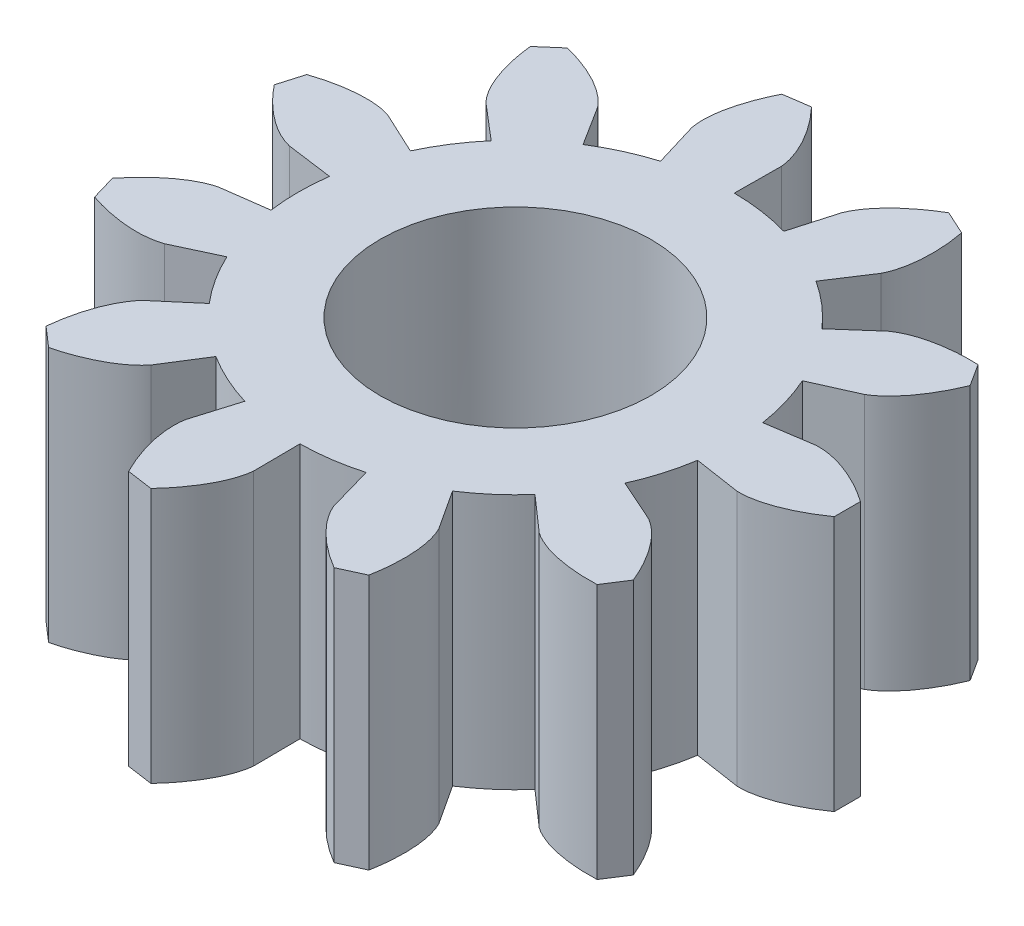
SolidWorks part; units mm, degrees
ref_plane "Front Plane" through (0, 0, 0) normal (0, 0, 1) x (1, 0, 0)
ref_plane "Top Plane" through (0, 0, 0) normal (0, 1, 0) x (1, 0, 0)
ref_plane "Right Plane" through (0, 0, 0) normal (1, 0, 0) x (0, 0, -1)
ref_plane "Plane1" through (0, -5, 0) normal (0, -1, 0) x (1, 0, 0)
sketch "Sketch1" plane through (0, -5, 0) normal (0, -1, 0) x (1, 0, 0)
  line L0 (3.1902, -2.808) -> (3.8796, -3.4147)
  line L1 (5.3253, -3.727) -> (5.6025, -3.2958)
  line L2 (4.7178, -2.1104) -> (3.8795, -1.7354)
  line L3 (4.2019, -0.6375) -> (5.1098, -0.7752)
  line L4 (6.4949, -0.2563) -> (6.4949, 0.2563)
  line L5 (5.1098, 0.7752) -> (4.2019, 0.6375)
  line L6 (3.8795, 1.7354) -> (4.7178, 2.1104)
  line L7 (5.6025, 3.2958) -> (5.3253, 3.727)
  line L8 (3.8796, 3.4147) -> (3.1902, 2.808)
  line L9 (2.3254, 3.5574) -> (2.8279, 4.326)
  line L10 (2.9312, 5.8015) -> (2.465, 6.0145)
  line L11 (1.4175, 4.9701) -> (1.1657, 4.087)
  line L12 (0.033, 4.2499) -> (0.0401, 5.1682)
  line L13 (-0.6706, 6.4653) -> (-1.178, 6.3924)
  line L14 (-1.4945, 4.9475) -> (-1.229, 4.0684)
  line L15 (-2.2699, 3.5931) -> (-2.7604, 4.3694)
  line L16 (-4.0596, 5.0764) -> (-4.447, 4.7407)
  line L17 (-3.9321, 3.3541) -> (-3.2334, 2.7581)
  line L18 (-3.8521, 1.7955) -> (-4.6844, 2.1834)
  line L19 (-6.1596, 2.0758) -> (-6.3041, 1.5839)
  line L20 (-5.1213, 0.6958) -> (-4.2113, 0.5722)
  line L21 (-4.2113, -0.5722) -> (-5.1213, -0.6958)
  line L22 (-6.3041, -1.5839) -> (-6.1596, -2.0758)
  line L23 (-4.6844, -2.1834) -> (-3.8521, -1.7955)
  line L24 (-3.2334, -2.7581) -> (-3.9321, -3.3541)
  line L25 (-4.447, -4.7407) -> (-4.0596, -5.0764)
  line L26 (-2.7604, -4.3694) -> (-2.2699, -3.5931)
  line L27 (-1.229, -4.0684) -> (-1.4945, -4.9475)
  line L28 (-1.178, -6.3924) -> (-0.6706, -6.4653)
  line L29 (0.0401, -5.1682) -> (0.033, -4.2499)
  line L30 (1.1657, -4.087) -> (1.4175, -4.9701)
  line L31 (2.465, -6.0145) -> (2.9312, -5.8015)
  line L32 (2.8279, -4.326) -> (2.3254, -3.5574)
  arc A0 (2.3254, -3.5574) -> (3.1902, -2.808) centre (0, 0) ccw
  arc A1 (3.8795, -1.7354) -> (4.2019, -0.6375) centre (0, 0) ccw
  arc A2 (4.2019, 0.6375) -> (3.8795, 1.7354) centre (0, 0) ccw
  arc A3 (3.1902, 2.808) -> (2.3254, 3.5574) centre (0, 0) ccw
  arc A4 (1.1657, 4.087) -> (0.033, 4.2499) centre (0, 0) ccw
  arc A5 (-1.229, 4.0684) -> (-2.2699, 3.5931) centre (0, 0) ccw
  arc A6 (-3.2334, 2.7581) -> (-3.8521, 1.7955) centre (0, 0) ccw
  arc A7 (-4.2113, 0.5722) -> (-4.2113, -0.5722) centre (0, 0) ccw
  arc A8 (-3.8521, -1.7955) -> (-3.2334, -2.7581) centre (0, 0) ccw
  arc A9 (-2.2699, -3.5931) -> (-1.229, -4.0684) centre (0, 0) ccw
  arc A10 (0.033, -4.2499) -> (1.1657, -4.087) centre (0, 0) ccw
  ellipse E0 centre (5.2837, -2.9889) end of major axis (6.9215, -2.923) minor radius 0.7393 (3.8796, -3.4147) -> (5.3253, -3.727) ccw
  ellipse E1 centre (4.9239, -3.5316) end of major axis (5.5451, -5.0133) minor radius 0.7173 (5.6025, -3.2958) -> (4.7178, -2.1104) ccw
  ellipse E2 centre (6.0609, 0.3422) end of major axis (7.403, 1.283) minor radius 0.7393 (5.1098, -0.7752) -> (6.4949, -0.2563) ccw
  ellipse E3 centre (6.0515, -0.3089) end of major axis (7.3752, -1.2195) minor radius 0.7173 (6.4949, 0.2563) -> (5.1098, 0.7752) ccw
  ellipse E4 centre (4.9137, 3.5646) end of major axis (4.2933, 2.0475) minor radius 0.7393 (4.7178, 2.1104) -> (5.6025, 3.2958) ccw
  ellipse E5 centre (5.2579, 3.0118) end of major axis (6.8637, 2.9614) minor radius 0.7173 (5.3253, 3.727) -> (3.8796, 3.4147) ccw
  ellipse E6 centre (2.2065, 5.6553) end of major axis (2.5048, 4.0436) minor radius 0.7393 (2.8279, 4.326) -> (2.9312, 5.8015) ccw
  ellipse E7 centre (2.7949, 5.3763) end of major axis (4.1731, 6.2021) minor radius 0.7173 (2.465, 6.0145) -> (1.4175, 4.9701) ccw
  ellipse E8 centre (-1.2013, 5.9505) end of major axis (-0.079, 4.7559) minor radius 0.7393 (0.0401, 5.1682) -> (-0.6706, 6.4653) ccw
  ellipse E9 centre (-0.5554, 6.0339) end of major axis (-1.2684, 4.5942) minor radius 0.7173 (-1.178, 6.3924) -> (-1.4945, 4.9475) ccw
  ellipse E10 centre (-4.2276, 4.3564) end of major axis (-2.6377, 3.9582) minor radius 0.7393 (-2.7604, 4.3694) -> (-4.0596, 5.0764) ccw
  ellipse E11 centre (-3.7295, 4.7758) end of major axis (-3.5509, 3.1791) minor radius 0.7173 (-4.447, 4.7407) -> (-3.9321, 3.3541) ccw
  ellipse E12 centre (-5.9118, 1.3792) end of major axis (-4.3589, 1.9038) minor radius 0.7393 (-4.6844, 2.1834) -> (-6.1596, 2.0758) ccw
  ellipse E13 centre (-5.7194, 2.0013) end of major axis (-4.7059, 0.7547) minor radius 0.7173 (-6.3041, 1.5839) -> (-5.1213, 0.6958) ccw
  ellipse E14 centre (-5.7189, -2.0359) end of major axis (-6.7417, -3.3167) minor radius 0.7393 (-5.1213, -0.6958) -> (-6.3041, -1.5839) ccw
  ellipse E15 centre (-5.8934, -1.4085) end of major axis (-4.3669, -1.9093) minor radius 0.7173 (-6.1596, -2.0758) -> (-4.6844, -2.1834) ccw
  ellipse E16 centre (-3.7104, -4.8046) end of major axis (-3.8783, -6.435) minor radius 0.7393 (-3.9321, -3.3541) -> (-4.447, -4.7407) ccw
  ellipse E17 centre (-4.1964, -4.3712) end of major axis (-2.6414, -3.9671) minor radius 0.7173 (-4.0596, -5.0764) -> (-2.7604, -4.3694) ccw
  ellipse E18 centre (-0.5238, -6.0479) end of major axis (0.2164, -7.5103) minor radius 0.7393 (-1.4945, -4.9475) -> (-1.178, -6.3924) ccw
  ellipse E19 centre (-1.167, -5.946) end of major axis (-2.2567, -7.1265) minor radius 0.7173 (-0.6706, -6.4653) -> (0.0401, -5.1682) ccw
  ellipse E20 centre (2.829, -5.371) end of major axis (4.2424, -6.2011) minor radius 0.7393 (1.4175, -4.9701) -> (2.465, -6.0145) ccw
  ellipse E21 centre (2.2329, -5.633) end of major axis (1.9544, -7.2153) minor radius 0.7173 (2.9312, -5.8015) -> (2.8279, -4.326) ccw
  point P4 (5.2837, -2.9889)
  point P5 (6.9215, -2.923)
  point P6 (5.3134, -3.7275)
  point P7 (3.8796, -3.4147)
  point P8 (5.3253, -3.727)
  point P9 (4.5558, -3.6748)
  point P10 (6.0117, -2.3029)
  point P18 (4.9239, -3.5316)
  point P19 (5.5853, -3.2543)
  point P20 (5.5451, -5.0133)
  point P21 (5.6025, -3.2958)
  point P22 (4.7178, -2.1104)
  point P23 (5.2353, -2.6175)
  point P24 (4.6124, -4.4457)
  point P34 (6.0609, 0.3422)
  point P35 (7.403, 1.283)
  point P36 (6.4852, -0.2632)
  point P37 (5.1098, -0.7752)
  point P38 (6.4949, -0.2563)
  point P39 (5.8193, -0.6284)
  point P40 (6.3024, 1.3128)
  point P48 (6.0515, -0.3089)
  point P49 (7.3752, -1.2195)
  point P50 (5.645, -0.8998)
  point P51 (6.4949, 0.2563)
  point P52 (5.1098, 0.7752)
  point P53 (5.8193, 0.6284)
  point P54 (6.2837, -1.2463)
  point P64 (4.9137, 3.5646)
  point P65 (5.598, 3.2848)
  point P66 (4.2933, 2.0475)
  point P67 (4.7178, 2.1104)
  point P68 (5.6025, 3.2958)
  point P69 (5.2353, 2.6175)
  point P70 (4.5921, 4.5117)
  point P78 (5.2579, 3.0118)
  point P79 (6.8637, 2.9614)
  point P80 (5.2354, 2.2949)
  point P81 (5.3253, 3.727)
  point P82 (3.8796, 3.4147)
  point P83 (4.5558, 3.6748)
  point P84 (5.96, 2.3488)
  point P94 (2.2065, 5.6553)
  point P95 (2.9334, 5.7898)
  point P96 (2.5048, 4.0436)
  point P97 (2.8279, 4.326)
  point P98 (2.9312, 5.8015)
  point P99 (2.9891, 5.0324)
  point P100 (1.4239, 6.2782)
  point P108 (2.7949, 5.3763)
  point P109 (4.1731, 6.2021)
  point P110 (3.1635, 4.7611)
  point P111 (2.465, 6.0145)
  point P112 (1.4175, 4.9701)
  point P113 (1.8458, 5.5545)
  point P114 (3.744, 5.1982)
  point P124 (-1.2013, 5.9505)
  point P125 (-0.6625, 6.4566)
  point P126 (-0.079, 4.7559)
  point P127 (0.0401, 5.1682)
  point P128 (-0.6706, 6.4653)
  point P129 (-0.2061, 5.8496)
  point P130 (-2.1964, 6.0514)
  point P138 (-0.5554, 6.0339)
  point P139 (0.0873, 5.7156)
  point P140 (-1.2684, 4.5942)
  point P141 (-1.178, 6.3924)
  point P142 (-1.4945, 4.9475)
  point P143 (-1.4502, 5.6707)
  point P144 (0.3393, 6.3971)
  point P154 (-4.2276, 4.3564)
  point P155 (-2.6377, 3.9582)
  point P156 (-4.4072, 3.6393)
  point P157 (-2.7604, 4.3694)
  point P158 (-4.0596, 5.0764)
  point P159 (-3.3359, 4.8095)
  point P160 (-5.1193, 3.9033)
  point P168 (-3.7295, 4.7758)
  point P169 (-3.0166, 4.8555)
  point P170 (-3.5509, 3.1791)
  point P171 (-4.447, 4.7407)
  point P172 (-3.9321, 3.3541)
  point P173 (-4.2858, 3.9864)
  point P174 (-3.1731, 5.5651)
  point P184 (-5.9118, 1.3792)
  point P185 (-4.3589, 1.9038)
  point P186 (-5.6752, 0.6788)
  point P187 (-4.6844, 2.1834)
  point P188 (-6.1596, 2.0758)
  point P189 (-5.4066, 2.2425)
  point P190 (-6.4169, 0.5159)
  point P198 (-5.7194, 2.0013)
  point P199 (-5.1628, 2.4538)
  point P200 (-4.7059, 0.7547)
  point P201 (-6.3041, 1.5839)
  point P202 (-5.1213, 0.6958)
  point P203 (-5.7607, 1.0365)
  point P204 (-5.6781, 2.9661)
  point P214 (-5.7189, -2.0359)
  point P215 (-5.1413, -2.4972)
  point P216 (-6.7417, -3.3167)
  point P217 (-5.1213, -0.6958)
  point P218 (-6.3041, -1.5839)
  point P219 (-5.7607, -1.0365)
  point P220 (-5.6772, -3.0352)
  point P228 (-5.8934, -1.4085)
  point P229 (-4.3669, -1.9093)
  point P230 (-6.117, -2.09)
  point P231 (-6.1596, -2.0758)
  point P232 (-4.6844, -2.1834)
  point P233 (-5.4066, -2.2425)
  point P234 (-6.3803, -0.5745)
  point P244 (-3.7104, -4.8046)
  point P245 (-2.975, -4.8803)
  point P246 (-3.8783, -6.435)
  point P247 (-3.9321, -3.3541)
  point P248 (-4.447, -4.7407)
  point P249 (-4.2858, -3.9864)
  point P250 (-3.135, -5.6227)
  point P258 (-4.1964, -4.3712)
  point P259 (-2.6414, -3.9671)
  point P260 (-4.016, -5.0654)
  point P261 (-4.0596, -5.0764)
  point P262 (-2.7604, -4.3694)
  point P263 (-3.3359, -4.8095)
  point P264 (-5.0568, -3.9328)
  point P274 (-0.5238, -6.0479)
  point P275 (0.1357, -5.714)
  point P276 (0.2164, -7.5103)
  point P277 (-1.4945, -4.9475)
  point P278 (-1.178, -6.3924)
  point P279 (-1.4502, -5.6707)
  point P280 (0.4025, -6.4251)
  point P288 (-1.167, -5.946)
  point P289 (-0.6399, -6.4325)
  point P290 (-2.2567, -7.1265)
  point P291 (-0.6706, -6.4653)
  point P292 (0.0401, -5.1682)
  point P293 (-0.2061, -5.8496)
  point P294 (-2.1279, -6.0424)
  point P304 (2.829, -5.371)
  point P305 (4.2424, -6.2011)
  point P306 (2.4547, -6.0085)
  point P307 (1.4175, -4.9701)
  point P308 (2.465, -6.0145)
  point P309 (1.8458, -5.5545)
  point P310 (3.8123, -5.1875)
  point P318 (2.2329, -5.633)
  point P319 (2.9393, -5.7573)
  point P320 (1.9544, -7.2153)
  point P321 (2.9312, -5.8015)
  point P322 (2.8279, -4.326)
  point P323 (2.9891, -5.0324)
  point P324 (1.4767, -6.2336)
extrude "Boss-Extrude1" add sketch "Sketch1" against normal blind 5
sketch "Sketch2" plane through (0, 0, 0) normal (0, 1, 0) x (1, 0, 0)
  line L33 (2.3254, 3.5574) -> (2.8279, 4.326)
  line L34 (2.9312, 5.8015) -> (2.465, 6.0145)
  line L35 (1.4175, 4.9701) -> (1.1657, 4.087)
  line L36 (0.033, 4.2499) -> (0.0401, 5.1682)
  line L37 (-0.6706, 6.4653) -> (-1.178, 6.3924)
  line L38 (-1.4945, 4.9475) -> (-1.229, 4.0684)
  line L39 (-2.2699, 3.5931) -> (-2.7604, 4.3694)
  line L40 (-4.0596, 5.0764) -> (-4.447, 4.7407)
  line L41 (-3.9321, 3.3541) -> (-3.2334, 2.7581)
  line L42 (-3.8521, 1.7955) -> (-4.6844, 2.1834)
  line L43 (-6.1596, 2.0758) -> (-6.3041, 1.5839)
  line L44 (-5.1213, 0.6958) -> (-4.2113, 0.5722)
  line L45 (-4.2113, -0.5722) -> (-5.1213, -0.6958)
  line L46 (-6.3041, -1.5839) -> (-6.1596, -2.0758)
  line L47 (-4.6844, -2.1834) -> (-3.8521, -1.7955)
  line L48 (-3.2334, -2.7581) -> (-3.9321, -3.3541)
  line L49 (-4.447, -4.7407) -> (-4.0596, -5.0764)
  line L50 (-2.7604, -4.3694) -> (-2.2699, -3.5931)
  line L51 (-1.229, -4.0684) -> (-1.4945, -4.9475)
  line L52 (-1.178, -6.3924) -> (-0.6706, -6.4653)
  line L53 (0.0401, -5.1682) -> (0.033, -4.2499)
  line L54 (1.1657, -4.087) -> (1.4175, -4.9701)
  line L55 (2.465, -6.0145) -> (2.9312, -5.8015)
  line L56 (2.8279, -4.326) -> (2.3254, -3.5574)
  line L57 (3.1902, -2.808) -> (3.8796, -3.4147)
  line L58 (5.3253, -3.727) -> (5.6025, -3.2958)
  line L59 (4.7178, -2.1104) -> (3.8795, -1.7354)
  line L60 (4.2019, -0.6375) -> (5.1098, -0.7752)
  line L61 (6.4949, -0.2563) -> (6.4949, 0.2563)
  line L62 (5.1098, 0.7752) -> (4.2019, 0.6375)
  line L63 (3.8795, 1.7354) -> (4.7178, 2.1104)
  line L64 (5.6025, 3.2958) -> (5.3253, 3.727)
  line L65 (3.8796, 3.4147) -> (3.1902, 2.808)
  line L66 (2.3254, 3.5574) -> (2.8279, 4.326)
  line L67 (2.9312, 5.8015) -> (2.465, 6.0145)
  line L68 (1.4175, 4.9701) -> (1.1657, 4.087)
  line L69 (0.033, 4.2499) -> (0.0401, 5.1682)
  line L70 (-0.6706, 6.4653) -> (-1.178, 6.3924)
  line L71 (-1.4945, 4.9475) -> (-1.229, 4.0684)
  line L72 (-2.2699, 3.5931) -> (-2.7604, 4.3694)
  line L73 (-4.0596, 5.0764) -> (-4.447, 4.7407)
  line L74 (-3.9321, 3.3541) -> (-3.2334, 2.7581)
  line L75 (-3.8521, 1.7955) -> (-4.6844, 2.1834)
  line L76 (-6.1596, 2.0758) -> (-6.3041, 1.5839)
  line L77 (-5.1213, 0.6958) -> (-4.2113, 0.5722)
  line L78 (-4.2113, -0.5722) -> (-5.1213, -0.6958)
  line L79 (-6.3041, -1.5839) -> (-6.1596, -2.0758)
  line L80 (-4.6844, -2.1834) -> (-3.8521, -1.7955)
  line L81 (-3.2334, -2.7581) -> (-3.9321, -3.3541)
  line L82 (-4.447, -4.7407) -> (-4.0596, -5.0764)
  line L83 (-2.7604, -4.3694) -> (-2.2699, -3.5931)
  line L84 (-1.229, -4.0684) -> (-1.4945, -4.9475)
  line L85 (-1.178, -6.3924) -> (-0.6706, -6.4653)
  line L86 (0.0401, -5.1682) -> (0.033, -4.2499)
  line L87 (1.1657, -4.087) -> (1.4175, -4.9701)
  line L88 (2.465, -6.0145) -> (2.9312, -5.8015)
  line L89 (2.8279, -4.326) -> (2.3254, -3.5574)
  line L90 (3.1902, -2.808) -> (3.8796, -3.4147)
  line L91 (5.3253, -3.727) -> (5.6025, -3.2958)
  line L92 (4.7178, -2.1104) -> (3.8795, -1.7354)
  line L93 (4.2019, -0.6375) -> (5.1098, -0.7752)
  line L94 (6.4949, -0.2563) -> (6.4949, 0.2563)
  line L95 (5.1098, 0.7752) -> (4.2019, 0.6375)
  line L96 (3.8795, 1.7354) -> (4.7178, 2.1104)
  line L97 (5.6025, 3.2958) -> (5.3253, 3.727)
  line L98 (3.8796, 3.4147) -> (3.1902, 2.808)
  circle A0 centre (0, 0) radius 2.65
  arc A11 (3.1902, 2.808) -> (2.3254, 3.5574) centre (0, 0) ccw
  arc A12 (1.1657, 4.087) -> (0.033, 4.2499) centre (0, 0) ccw
  arc A13 (-1.229, 4.0684) -> (-2.2699, 3.5931) centre (0, 0) ccw
  arc A14 (-3.2334, 2.7581) -> (-3.8521, 1.7955) centre (0, 0) ccw
  arc A15 (-4.2113, 0.5722) -> (-4.2113, -0.5722) centre (0, 0) ccw
  arc A16 (-3.8521, -1.7955) -> (-3.2334, -2.7581) centre (0, 0) ccw
  arc A17 (-2.2699, -3.5931) -> (-1.229, -4.0684) centre (0, 0) ccw
  arc A18 (0.033, -4.2499) -> (1.1657, -4.087) centre (0, 0) ccw
  arc A19 (2.3254, -3.5574) -> (3.1902, -2.808) centre (0, 0) ccw
  arc A20 (3.8795, -1.7354) -> (4.2019, -0.6375) centre (0, 0) ccw
  arc A21 (4.2019, 0.6375) -> (3.8795, 1.7354) centre (0, 0) ccw
  arc A22 (3.1902, 2.808) -> (2.3254, 3.5574) centre (0, 0) ccw
  arc A23 (1.1657, 4.087) -> (0.033, 4.2499) centre (0, 0) ccw
  arc A24 (-1.229, 4.0684) -> (-2.2699, 3.5931) centre (0, 0) ccw
  arc A25 (-3.2334, 2.7581) -> (-3.8521, 1.7955) centre (0, 0) ccw
  arc A26 (-4.2113, 0.5722) -> (-4.2113, -0.5722) centre (0, 0) ccw
  arc A27 (-3.8521, -1.7955) -> (-3.2334, -2.7581) centre (0, 0) ccw
  arc A28 (-2.2699, -3.5931) -> (-1.229, -4.0684) centre (0, 0) ccw
  arc A29 (0.033, -4.2499) -> (1.1657, -4.087) centre (0, 0) ccw
  arc A30 (2.3254, -3.5574) -> (3.1902, -2.808) centre (0, 0) ccw
  arc A31 (3.8795, -1.7354) -> (4.2019, -0.6375) centre (0, 0) ccw
  arc A32 (4.2019, 0.6375) -> (3.8795, 1.7354) centre (0, 0) ccw
  ellipse E22 centre (2.2329, 5.633) end of major axis (1.9544, 7.2153) minor radius 0.7173 (2.8279, 4.326) -> (2.9312, 5.8015) ccw
  ellipse E23 centre (2.829, 5.371) end of major axis (4.2424, 6.2011) minor radius 0.7393 (2.465, 6.0145) -> (1.4175, 4.9701) ccw
  ellipse E24 centre (-1.167, 5.946) end of major axis (-2.2567, 7.1265) minor radius 0.7173 (0.0401, 5.1682) -> (-0.6706, 6.4653) ccw
  ellipse E25 centre (-0.5238, 6.0479) end of major axis (0.2164, 7.5103) minor radius 0.7393 (-1.178, 6.3924) -> (-1.4945, 4.9475) ccw
  ellipse E26 centre (-4.1964, 4.3712) end of major axis (-2.6414, 3.9671) minor radius 0.7173 (-2.7604, 4.3694) -> (-4.0596, 5.0764) ccw
  ellipse E27 centre (-3.7104, 4.8046) end of major axis (-3.8783, 6.435) minor radius 0.7393 (-4.447, 4.7407) -> (-3.9321, 3.3541) ccw
  ellipse E28 centre (-5.8934, 1.4085) end of major axis (-4.3669, 1.9093) minor radius 0.7173 (-4.6844, 2.1834) -> (-6.1596, 2.0758) ccw
  ellipse E29 centre (-5.7189, 2.0359) end of major axis (-6.7417, 3.3167) minor radius 0.7393 (-6.3041, 1.5839) -> (-5.1213, 0.6958) ccw
  ellipse E30 centre (-5.7194, -2.0013) end of major axis (-4.7059, -0.7547) minor radius 0.7173 (-5.1213, -0.6958) -> (-6.3041, -1.5839) ccw
  ellipse E31 centre (-5.9118, -1.3792) end of major axis (-4.3589, -1.9038) minor radius 0.7393 (-6.1596, -2.0758) -> (-4.6844, -2.1834) ccw
  ellipse E32 centre (-3.7295, -4.7758) end of major axis (-3.5509, -3.1791) minor radius 0.7173 (-3.9321, -3.3541) -> (-4.447, -4.7407) ccw
  ellipse E33 centre (-4.2276, -4.3564) end of major axis (-2.6377, -3.9582) minor radius 0.7393 (-4.0596, -5.0764) -> (-2.7604, -4.3694) ccw
  ellipse E34 centre (-0.5554, -6.0339) end of major axis (-1.2684, -4.5942) minor radius 0.7173 (-1.4945, -4.9475) -> (-1.178, -6.3924) ccw
  ellipse E35 centre (-1.2013, -5.9505) end of major axis (-0.079, -4.7559) minor radius 0.7393 (-0.6706, -6.4653) -> (0.0401, -5.1682) ccw
  ellipse E36 centre (2.7949, -5.3763) end of major axis (4.1731, -6.2021) minor radius 0.7173 (1.4175, -4.9701) -> (2.465, -6.0145) ccw
  ellipse E37 centre (2.2065, -5.6553) end of major axis (2.5048, -4.0436) minor radius 0.7393 (2.9312, -5.8015) -> (2.8279, -4.326) ccw
  ellipse E38 centre (5.2579, -3.0118) end of major axis (3.6521, -3.0623) minor radius 0.7173 (3.8796, -3.4147) -> (5.3253, -3.727) ccw
  ellipse E39 centre (4.9137, -3.5646) end of major axis (4.2933, -2.0475) minor radius 0.7393 (5.6025, -3.2958) -> (4.7178, -2.1104) ccw
  ellipse E40 centre (6.0515, 0.3089) end of major axis (4.7279, -0.6017) minor radius 0.7173 (5.1098, -0.7752) -> (6.4949, -0.2563) ccw
  ellipse E41 centre (6.0609, -0.3422) end of major axis (7.403, -1.283) minor radius 0.7393 (6.4949, 0.2563) -> (5.1098, 0.7752) ccw
  ellipse E42 centre (4.9239, 3.5316) end of major axis (5.5451, 5.0133) minor radius 0.7173 (4.7178, 2.1104) -> (5.6025, 3.2958) ccw
  ellipse E43 centre (5.2837, 2.9889) end of major axis (3.646, 3.0547) minor radius 0.7393 (5.3253, 3.727) -> (3.8796, 3.4147) ccw
  ellipse E44 centre (2.2329, 5.633) end of major axis (1.9544, 7.2153) minor radius 0.7173 (2.8279, 4.326) -> (2.9312, 5.8015) ccw
  ellipse E45 centre (2.829, 5.371) end of major axis (4.2424, 6.2011) minor radius 0.7393 (2.465, 6.0145) -> (1.4175, 4.9701) ccw
  ellipse E46 centre (-1.167, 5.946) end of major axis (-2.2567, 7.1265) minor radius 0.7173 (0.0401, 5.1682) -> (-0.6706, 6.4653) ccw
  ellipse E47 centre (-0.5238, 6.0479) end of major axis (0.2164, 7.5103) minor radius 0.7393 (-1.178, 6.3924) -> (-1.4945, 4.9475) ccw
  ellipse E48 centre (-4.1964, 4.3712) end of major axis (-2.6414, 3.9671) minor radius 0.7173 (-2.7604, 4.3694) -> (-4.0596, 5.0764) ccw
  ellipse E49 centre (-3.7104, 4.8046) end of major axis (-3.8783, 6.435) minor radius 0.7393 (-4.447, 4.7407) -> (-3.9321, 3.3541) ccw
  ellipse E50 centre (-5.8934, 1.4085) end of major axis (-4.3669, 1.9093) minor radius 0.7173 (-4.6844, 2.1834) -> (-6.1596, 2.0758) ccw
  ellipse E51 centre (-5.7189, 2.0359) end of major axis (-6.7417, 3.3167) minor radius 0.7393 (-6.3041, 1.5839) -> (-5.1213, 0.6958) ccw
  ellipse E52 centre (-5.7194, -2.0013) end of major axis (-4.7059, -0.7547) minor radius 0.7173 (-5.1213, -0.6958) -> (-6.3041, -1.5839) ccw
  ellipse E53 centre (-5.9118, -1.3792) end of major axis (-4.3589, -1.9038) minor radius 0.7393 (-6.1596, -2.0758) -> (-4.6844, -2.1834) ccw
  ellipse E54 centre (-3.7295, -4.7758) end of major axis (-3.5509, -3.1791) minor radius 0.7173 (-3.9321, -3.3541) -> (-4.447, -4.7407) ccw
  ellipse E55 centre (-4.2276, -4.3564) end of major axis (-2.6377, -3.9582) minor radius 0.7393 (-4.0596, -5.0764) -> (-2.7604, -4.3694) ccw
  ellipse E56 centre (-0.5554, -6.0339) end of major axis (-1.2684, -4.5942) minor radius 0.7173 (-1.4945, -4.9475) -> (-1.178, -6.3924) ccw
  ellipse E57 centre (-1.2013, -5.9505) end of major axis (-0.079, -4.7559) minor radius 0.7393 (-0.6706, -6.4653) -> (0.0401, -5.1682) ccw
  ellipse E58 centre (2.7949, -5.3763) end of major axis (4.1731, -6.2021) minor radius 0.7173 (1.4175, -4.9701) -> (2.465, -6.0145) ccw
  ellipse E59 centre (2.2065, -5.6553) end of major axis (2.5048, -4.0436) minor radius 0.7393 (2.9312, -5.8015) -> (2.8279, -4.326) ccw
  ellipse E60 centre (5.2579, -3.0118) end of major axis (6.8637, -2.9614) minor radius 0.7173 (3.8796, -3.4147) -> (5.3253, -3.727) ccw
  ellipse E61 centre (4.9137, -3.5646) end of major axis (4.2933, -2.0475) minor radius 0.7393 (5.6025, -3.2958) -> (4.7178, -2.1104) ccw
  ellipse E62 centre (6.0515, 0.3089) end of major axis (7.3752, 1.2195) minor radius 0.7173 (5.1098, -0.7752) -> (6.4949, -0.2563) ccw
  ellipse E63 centre (6.0609, -0.3422) end of major axis (7.403, -1.283) minor radius 0.7393 (6.4949, 0.2563) -> (5.1098, 0.7752) ccw
  ellipse E64 centre (4.9239, 3.5316) end of major axis (5.5451, 5.0133) minor radius 0.7173 (4.7178, 2.1104) -> (5.6025, 3.2958) ccw
  ellipse E65 centre (5.2837, 2.9889) end of major axis (6.9215, 2.923) minor radius 0.7393 (5.3253, 3.727) -> (3.8796, 3.4147) ccw
  dimension "D2" = 5.3
  dimension "D1" = 0
extrude "Cut-Extrude1" cut sketch "Sketch2" against normal through all both and the other way through all contours A0
